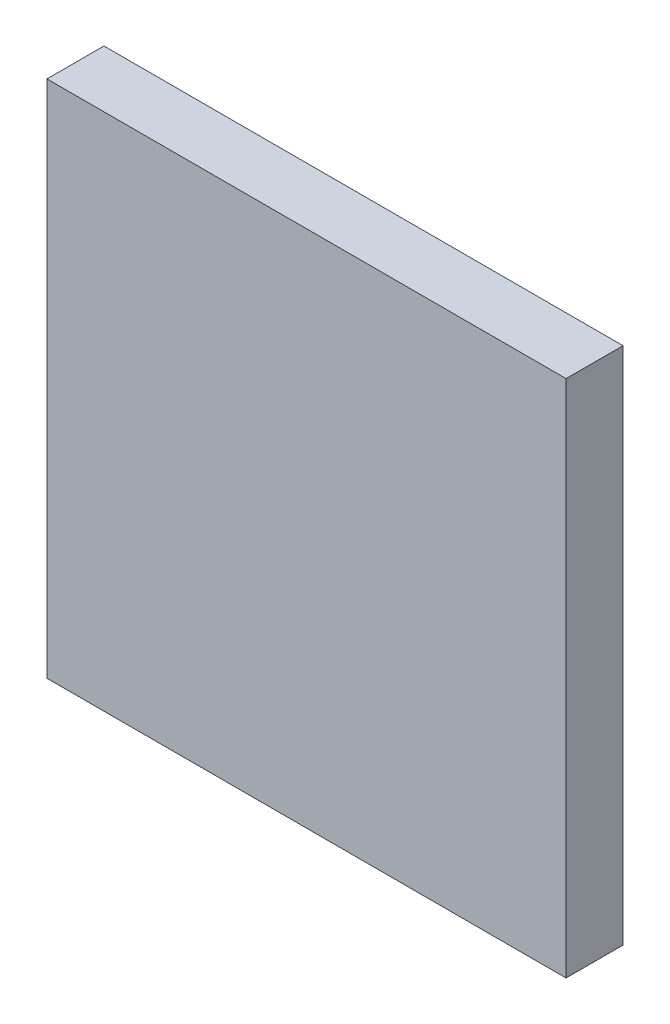
SolidWorks part; units mm, degrees
ref_plane "Front Plane" through (0, 0, 0) normal (0, 0, 1) x (1, 0, 0)
ref_plane "Top Plane" through (0, 0, 0) normal (0, 1, 0) x (1, 0, 0)
ref_plane "Right Plane" through (0, 0, 0) normal (1, 0, 0) x (0, 0, -1)
sketch "Sketch1" plane through (0, 0, 0) normal (0, 0, 1) x (1, 0, 0)
  line L1 (-20.5, -20.5) -> (20.5, -20.5)
  line L2 (-20.5, -20.5) -> (-20.5, 20.5)
  line L3 (-20.5, 20.5) -> (20.5, 20.5)
  line L4 (20.5, -20.5) -> (20.5, 20.5)
  line L5 (-20.5, -20.5) -> (20.5, 20.5) construction
  line L6 (-20.5, 20.5) -> (20.5, -20.5) construction
  point P0 (0, 0)
extrude "Boss-Extrude1" add sketch "Sketch1" along normal blind 4.5
sketch "Sketch3" plane through (0, 0, 0) normal (0, 0, 1) x (1, 0, 0)
  line L0 (20.5, -20.5) -> (20.5, 20.5) construction
  line L1 (25, -11.5) -> (20.5, -11.5)
  line L2 (25, -11.5) -> (25, -16)
  line L3 (25, -16) -> (20.5, -16)
  line L4 (20.5, -11.5) -> (20.5, -16)
  line L5 (25, -11.5) -> (20.5, -16) construction
  line L6 (25, -16) -> (20.5, -11.5) construction
  line L7 (-20.5, -20.5) -> (20.5, -20.5) construction
  line L8 (25, -2.5) -> (25, -7)
  line L9 (25, -2.5) -> (20.5, -2.5)
  line L10 (20.5, -2.5) -> (20.5, -7)
  line L11 (25, -7) -> (20.5, -7)
  line L12 (-0.4278, -20.5) -> (-0.4278, 20.5) construction
  line L21 (-20.5, -20.5) -> (20.5, -20.5) construction
  line L22 (20.5, 20.5) -> (-20.5, 20.5) construction
  line L23 (20.5, 0) -> (-20.5, 0) construction
  line L24 (-20.5, 20.5) -> (-20.5, -20.5) construction
  point P0 (22.75, -13.75)
  point P5 (22.75, -16)
  point P28 (20.5, -20.5)
